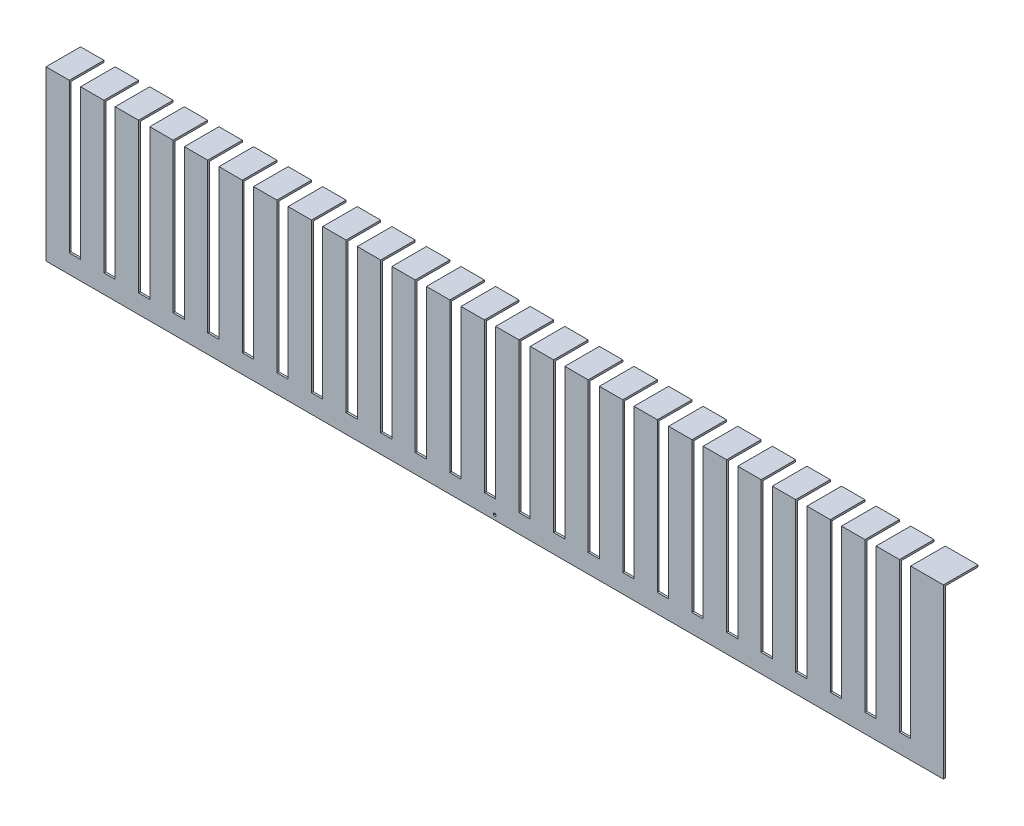
SolidWorks part; units mm, degrees
material "AISI 4130 Steel, annealed at 865C"
ref_plane "Front Plane" through (0, 0, 0) normal (0, 0, 1) x (1, 0, 0)
ref_plane "Top Plane" through (0, 0, 0) normal (0, 1, 0) x (1, 0, 0)
ref_plane "Right Plane" through (0, 0, 0) normal (1, 0, 0) x (0, 0, -1)
sketch "Sketch1" plane through (0, 0, 0) normal (0, 0, 1) x (1, 0, 0)
  line L0 (-480, 80) -> (-455, 80)
  line L1 (-480, -100) -> (480, -100)
  line L2 (-480, -100) -> (-480, 80)
  line L4 (480, -100) -> (480, 80)
  line L6 (-443, 80) -> (-418, 80)
  line L8 (-455, 80) -> (-455, -80)
  line L9 (-455, -80) -> (-443, -80)
  line L10 (-443, 80) -> (-443, -80)
  line L11 (-469.94, 80) -> (-455, 80)
  line L13 (-418, 80) -> (-418, -80)
  line L14 (-418, -80) -> (-406, -80)
  line L16 (-406, 80) -> (-406, -80)
  line L17 (-406, 80) -> (-381, 80)
  line L18 (-381, 80) -> (-381, -80)
  line L20 (-381, -80) -> (-369, -80)
  line L21 (-369, 80) -> (-369, -80)
  line L22 (-369, 80) -> (-344, 80)
  line L23 (-344, 80) -> (-344, -80)
  line L24 (-344, -80) -> (-332, -80)
  line L25 (-332, 80) -> (-332, -80)
  line L26 (-332, 80) -> (-307, 80)
  line L27 (-307, 80) -> (-307, -80)
  line L28 (-307, -80) -> (-295, -80)
  line L29 (-295, 80) -> (-295, -80)
  line L30 (-295, 80) -> (-270, 80)
  line L31 (-270, 80) -> (-270, -80)
  line L32 (-270, -80) -> (-258, -80)
  line L33 (-258, 80) -> (-258, -80)
  line L34 (-258, 80) -> (-233, 80)
  line L35 (-233, 80) -> (-233, -80)
  line L36 (-233, -80) -> (-221, -80)
  line L37 (-221, 80) -> (-221, -80)
  line L38 (-221, 80) -> (-196, 80)
  line L39 (-196, 80) -> (-196, -80)
  line L40 (-196, -80) -> (-184, -80)
  line L41 (-184, 80) -> (-184, -80)
  line L42 (-184, 80) -> (-159, 80)
  line L43 (-159, 80) -> (-159, -80)
  line L44 (-159, -80) -> (-147, -80)
  line L45 (-147, 80) -> (-147, -80)
  line L46 (-147, 80) -> (-122, 80)
  line L47 (-122, 80) -> (-122, -80)
  line L48 (-122, -80) -> (-110, -80)
  line L49 (-110, 80) -> (-110, -80)
  line L50 (-110, 80) -> (-85, 80)
  line L51 (-85, 80) -> (-85, -80)
  line L52 (-85, -80) -> (-73, -80)
  line L53 (-73, 80) -> (-73, -80)
  line L54 (-73, 80) -> (-48, 80)
  line L55 (-48, 80) -> (-48, -80)
  line L56 (-48, -80) -> (-36, -80)
  line L57 (-36, 80) -> (-36, -80)
  line L58 (-36, 80) -> (-11, 80)
  line L59 (-11, 80) -> (-11, -80)
  line L60 (-11, -80) -> (1, -80)
  line L61 (1, 80) -> (1, -80)
  line L62 (1, 80) -> (26, 80)
  line L63 (26, 80) -> (26, -80)
  line L64 (26, -80) -> (38, -80)
  line L65 (38, 80) -> (38, -80)
  line L66 (38, 80) -> (63, 80)
  line L67 (63, 80) -> (63, -80)
  line L68 (63, -80) -> (75, -80)
  line L69 (75, 80) -> (75, -80)
  line L70 (75, 80) -> (100, 80)
  line L71 (100, 80) -> (100, -80)
  line L72 (100, -80) -> (112, -80)
  line L73 (112, 80) -> (112, -80)
  line L74 (112, 80) -> (137, 80)
  line L75 (137, 80) -> (137, -80)
  line L76 (137, -80) -> (149, -80)
  line L77 (149, 80) -> (149, -80)
  line L78 (149, 80) -> (174, 80)
  line L79 (174, 80) -> (174, -80)
  line L80 (174, -80) -> (186, -80)
  line L81 (186, 80) -> (186, -80)
  line L82 (186, 80) -> (211, 80)
  line L83 (211, 80) -> (211, -80)
  line L84 (211, -80) -> (223, -80)
  line L85 (223, 80) -> (223, -80)
  line L86 (223, 80) -> (248, 80)
  line L87 (248, 80) -> (248, -80)
  line L88 (248, -80) -> (260, -80)
  line L89 (260, 80) -> (260, -80)
  line L90 (260, 80) -> (285, 80)
  line L91 (285, 80) -> (285, -80)
  line L92 (285, -80) -> (297, -80)
  line L93 (297, 80) -> (297, -80)
  line L94 (297, 80) -> (322, 80)
  line L95 (322, 80) -> (322, -80)
  line L96 (322, -80) -> (334, -80)
  line L97 (334, 80) -> (334, -80)
  line L98 (334, 80) -> (359, 80)
  line L99 (359, 80) -> (359, -80)
  line L100 (359, -80) -> (371, -80)
  line L101 (371, 80) -> (371, -80)
  line L102 (371, 80) -> (396, 80)
  line L103 (396, 80) -> (396, -80)
  line L104 (396, -80) -> (408, -80)
  line L105 (408, 80) -> (408, -80)
  line L106 (408, 80) -> (433, 80)
  line L107 (433, 80) -> (433, -80)
  line L108 (433, -80) -> (445, -80)
  line L109 (445, 80) -> (445, -80)
  line L110 (445, 80) -> (480, 80)
  line L127 (0, -20) -> (480, -100) construction
  line L147 (0, -20) -> (480, 80) construction
  line L388 (-151.26, -34.9763) -> (-151.26, -80) [skipped]
  line L389 (-163.26, -36.0958) -> (-163.26, -80) [skipped]
  line L390 (-161.32, -37.0721) -> (-161.32, -80) [skipped]
  line L391 (-173.32, -38.1917) -> (-173.32, -80) [skipped]
  line L392 (-171.38, -39.168) -> (-171.38, -80) [skipped]
  line L393 (-183.38, -40.2875) -> (-183.38, -80) [skipped]
  line L394 (-181.44, -41.2638) -> (-181.44, -80) [skipped]
  line L395 (-193.44, -42.3833) -> (-193.44, -80) [skipped]
  line L396 (-191.5, -43.3596) -> (-191.5, -80) [skipped]
  line L397 (-203.5, -80) -> (-191.5, -80) [skipped]
  line L398 (-213.56, -80) -> (-201.56, -80) [skipped]
  line L399 (-213.56, -46.575) -> (-213.56, -80) [skipped]
  line L400 (-211.62, -47.5513) -> (-211.62, -80) [skipped]
  line L401 (-223.62, -48.6708) -> (-223.62, -80) [skipped]
  line L402 (-221.68, -49.6471) -> (-221.68, -80) [skipped]
  line L403 (-233.68, -50.7667) -> (-233.68, -80) [skipped]
  line L404 (-231.74, -51.743) -> (-231.74, -80) [skipped]
  line L405 (-243.74, -52.8625) -> (-243.74, -80) [skipped]
  line L406 (-241.8, -53.8388) -> (-241.8, -80) [skipped]
  line L407 (-253.8, -54.9583) -> (-253.8, -80) [skipped]
  line L408 (-251.86, -55.9346) -> (-251.86, -80) [skipped]
  line L409 (-263.86, -57.0542) -> (-263.86, -80) [skipped]
  line L410 (-223.62, -80) -> (-211.62, -80) [skipped]
  line L411 (-263.86, -80) -> (-251.86, -80) [skipped]
  line L412 (-243.74, -80) -> (-231.74, -80) [skipped]
  line L413 (-253.8, -80) -> (-241.8, -80) [skipped]
  line L414 (-233.68, -80) -> (-221.68, -80) [skipped]
  line L415 (-201.56, -45.4555) -> (-201.56, -80) [skipped]
  line L416 (-203.5, -44.4792) -> (-203.5, -80) [skipped]
  line L417 (-183.38, -80) -> (-171.38, -80) [skipped]
  line L418 (-193.44, -80) -> (-181.44, -80) [skipped]
  line L419 (-173.32, -80) -> (-161.32, -80) [skipped]
  line L420 (-163.26, -80) -> (-151.26, -80) [skipped]
  line L421 (-294.04, 100) -> (-294.04, 63.3417) [skipped]
  line L422 (-292.1, 100) -> (-292.1, 64.318) [skipped]
  line L423 (-304.1, 100) -> (-304.1, 65.4375) [skipped]
  line L424 (-302.16, 100) -> (-302.16, 66.4138) [skipped]
  line L425 (-314.16, 100) -> (-314.16, 67.5333) [skipped]
  line L426 (-312.22, 100) -> (-312.22, 68.5096) [skipped]
  line L427 (-324.22, 100) -> (-324.22, 69.6292) [skipped]
  line L428 (-322.28, 100) -> (-322.28, 70.6055) [skipped]
  line L429 (-334.28, 100) -> (-334.28, 71.725) [skipped]
  line L430 (-282.04, 100) -> (-282.04, 62.2221) [skipped]
  line L431 (-283.98, 100) -> (-283.98, 61.2458) [skipped]
  line L432 (-271.98, 100) -> (-271.98, 60.1263) [skipped]
  line L433 (-273.92, 100) -> (-273.92, 59.15) [skipped]
  line L434 (-288.86, 80) -> (-283.92, 80) [skipped]
  line L435 (-288.86, 80) -> (-278.8, 80) [skipped]
  line L436 (-208.38, 80) -> (-203.44, 80) [skipped]
  line L437 (-238.56, 80) -> (-233.62, 80) [skipped]
  line L438 (-248.62, 80) -> (-243.68, 80) [skipped]
  line L439 (-248.62, 80) -> (-238.56, 80) [skipped]
  line L440 (-268.74, 80) -> (-263.8, 80) [skipped]
  line L441 (-268.74, 80) -> (-263.8, 80) [skipped]
  line L442 (-228.5, 80) -> (-223.56, 80) [skipped]
  line L443 (-213.5, 80) -> (-208.38, 80) [skipped]
  line L444 (-198.32, 80) -> (-193.38, 80) [skipped]
  line L445 (-188.26, 80) -> (-183.32, 80) [skipped]
  line L446 (-273.92, -80) -> (-261.92, -80) [skipped]
  line L447 (-261.92, -58.0305) -> (-261.92, -80) [skipped]
  line L448 (-294.04, -80) -> (-282.04, -80) [skipped]
  line L449 (-364.46, -80) -> (-352.46, -80) [skipped]
  line L450 (-344.34, -80) -> (-332.34, -80) [skipped]
  line L451 (-434.88, 80) -> (-434.88, -80) [skipped]
  line L452 (-434.88, -80) -> (-422.88, -80) [skipped]
  line L453 (-422.88, 80) -> (-422.88, -80) [skipped]
  line L454 (-424.82, 80) -> (-424.82, -80) [skipped]
  line L455 (-424.82, -80) -> (-412.82, -80) [skipped]
  line L456 (-412.82, 80) -> (-412.82, -80) [skipped]
  line L457 (-439.76, 80) -> (-414.76, 80) [skipped]
  line L458 (-414.76, 80) -> (-414.76, -80) [skipped]
  line L459 (-414.76, -80) -> (-402.76, -80) [skipped]
  line L460 (-402.76, 80) -> (-402.76, -80) [skipped]
  line L461 (-429.7, 80) -> (-404.7, 80) [skipped]
  line L462 (-404.7, 80) -> (-404.7, -80) [skipped]
  line L463 (-404.7, -80) -> (-392.7, -80) [skipped]
  line L464 (-392.7, 80) -> (-392.7, -80) [skipped]
  line L465 (-419.64, 80) -> (-394.64, 80) [skipped]
  line L466 (-394.64, 80) -> (-394.64, -80) [skipped]
  line L467 (-394.64, -80) -> (-382.64, -80) [skipped]
  line L468 (-382.64, 80) -> (-382.64, -80) [skipped]
  line L469 (-409.58, 80) -> (-384.58, 80) [skipped]
  line L470 (-384.58, 80) -> (-384.58, -80) [skipped]
  line L471 (-384.58, -80) -> (-372.58, -80) [skipped]
  line L472 (-372.58, 80) -> (-372.58, -80) [skipped]
  line L473 (-399.52, 80) -> (-374.52, 80) [skipped]
  line L474 (-374.52, 80) -> (-374.52, -80) [skipped]
  line L475 (-374.52, -80) -> (-362.52, -80) [skipped]
  line L476 (-362.52, 80) -> (-362.52, -80) [skipped]
  line L477 (-389.46, 80) -> (-364.46, 80) [skipped]
  line L478 (-364.46, 100) -> (-364.46, 78.0125) [skipped]
  line L479 (-352.46, 100) -> (-352.46, 76.893) [skipped]
  line L480 (-379.4, 80) -> (-354.4, 80) [skipped]
  line L481 (-354.4, 100) -> (-354.4, 75.9167) [skipped]
  line L482 (-354.4, -80) -> (-342.4, -80) [skipped]
  line L483 (-342.4, 100) -> (-342.4, 74.7971) [skipped]
  line L484 (-369.34, 80) -> (-344.34, 80) [skipped]
  line L485 (-344.34, 100) -> (-344.34, 73.8208) [skipped]
  line L486 (-332.34, 100) -> (-332.34, 72.7013) [skipped]
  line L487 (-359.28, 80) -> (-334.28, 80) [skipped]
  line L488 (-334.28, -80) -> (-322.28, -80) [skipped]
  line L489 (-349.22, 80) -> (-324.22, 80) [skipped]
  line L490 (-324.22, -80) -> (-312.22, -80) [skipped]
  line L491 (-339.16, 80) -> (-314.16, 80) [skipped]
  line L492 (-314.16, -80) -> (-302.16, -80) [skipped]
  line L493 (-329.1, 80) -> (-304.1, 80) [skipped]
  line L494 (-304.1, -80) -> (-292.1, -80) [skipped]
  line L495 (-319.04, 80) -> (-294.04, 80) [skipped]
  line L496 (-308.98, 80) -> (-304.04, 80) [skipped]
  line L497 (-283.98, -80) -> (-271.98, -80) [skipped]
  line L498 (-444.94, -80) -> (-432.94, -80) [skipped]
  line L499 (-432.94, 100) -> (-432.94, 93.6596) [skipped]
  line L500 (-444.94, 100) -> (-444.94, 94.7792) [skipped]
  line L501 (-449.82, 80) -> (-449.5662, 80) [skipped]
  line L502 (-459.88, 80) -> (-459.6262, 80) [skipped]
  circle A0 centre (0, -95) radius 1.5
  point P0 (0, 0)
  dimension "D4" = 3
  dimension "D1" = 180
  dimension "D2" = 960
  dimension "D3" = 5
  dimension "D5" = 25
  dimension "D7" = 160
  dimension "D8" = 12
  dimension "D6" = 30
  dimension "D9" = 25
extrude "Boss-Extrude1" add sketch "Sketch1" along normal blind 2
sketch "Sketch4" plane through (0, 80, 0) normal (0, 1, 0) x (1, 0, 0)
  line L0 (-418, 0) -> (-418, 35)
  line L1 (-455, 0) -> (-480, 0)
  line L2 (-455, 0) -> (-455, 35)
  line L3 (-455, 35) -> (-480, 35)
  line L4 (-480, 0) -> (-480, 35)
  line L5 (-418, 0) -> (-443, 0)
  line L6 (-443, 0) -> (-443, 35)
  line L7 (-418, 35) -> (-443, 35)
  line L8 (-381, 0) -> (-381, 35)
  line L9 (-381, 0) -> (-406, 0)
  line L10 (-406, 0) -> (-406, 35)
  line L11 (-381, 35) -> (-406, 35)
  line L12 (-344, 0) -> (-344, 35)
  line L13 (-344, 0) -> (-369, 0)
  line L14 (-369, 0) -> (-369, 35)
  line L15 (-344, 35) -> (-369, 35)
  line L16 (-307, 0) -> (-307, 35)
  line L17 (-307, 0) -> (-332, 0)
  line L18 (-332, 0) -> (-332, 35)
  line L19 (-307, 35) -> (-332, 35)
  line L20 (-270, 0) -> (-270, 35)
  line L21 (-270, 0) -> (-295, 0)
  line L22 (-295, 0) -> (-295, 35)
  line L23 (-270, 35) -> (-295, 35)
  line L24 (-233, 0) -> (-233, 35)
  line L25 (-233, 0) -> (-258, 0)
  line L26 (-258, 0) -> (-258, 35)
  line L27 (-233, 35) -> (-258, 35)
  line L28 (-196, 0) -> (-196, 35)
  line L29 (-196, 0) -> (-221, 0)
  line L30 (-221, 0) -> (-221, 35)
  line L31 (-196, 35) -> (-221, 35)
  line L32 (-159, 0) -> (-159, 35)
  line L33 (-159, 0) -> (-184, 0)
  line L34 (-184, 0) -> (-184, 35)
  line L35 (-159, 35) -> (-184, 35)
  line L36 (-122, 0) -> (-122, 35)
  line L37 (-122, 0) -> (-147, 0)
  line L38 (-147, 0) -> (-147, 35)
  line L39 (-122, 35) -> (-147, 35)
  line L40 (-85, 0) -> (-85, 35)
  line L41 (-85, 0) -> (-110, 0)
  line L42 (-110, 0) -> (-110, 35)
  line L43 (-85, 35) -> (-110, 35)
  line L44 (-48, 0) -> (-48, 35)
  line L45 (-48, 0) -> (-73, 0)
  line L46 (-73, 0) -> (-73, 35)
  line L47 (-48, 35) -> (-73, 35)
  line L48 (-11, 0) -> (-11, 35)
  line L49 (-11, 0) -> (-36, 0)
  line L50 (-36, 0) -> (-36, 35)
  line L51 (-11, 35) -> (-36, 35)
  line L52 (26, 0) -> (26, 35)
  line L53 (26, 0) -> (1, 0)
  line L54 (1, 0) -> (1, 35)
  line L55 (26, 35) -> (1, 35)
  line L56 (63, 0) -> (63, 35)
  line L57 (63, 0) -> (38, 0)
  line L58 (38, 0) -> (38, 35)
  line L59 (63, 35) -> (38, 35)
  line L60 (100, 0) -> (100, 35)
  line L61 (100, 0) -> (75, 0)
  line L62 (75, 0) -> (75, 35)
  line L63 (100, 35) -> (75, 35)
  line L64 (137, 0) -> (137, 35)
  line L65 (137, 0) -> (112, 0)
  line L66 (112, 0) -> (112, 35)
  line L67 (137, 35) -> (112, 35)
  line L68 (174, 0) -> (174, 35)
  line L69 (174, 0) -> (149, 0)
  line L70 (149, 0) -> (149, 35)
  line L71 (174, 35) -> (149, 35)
  line L72 (211, 0) -> (211, 35)
  line L73 (211, 0) -> (186, 0)
  line L74 (186, 0) -> (186, 35)
  line L75 (211, 35) -> (186, 35)
  line L76 (248, 0) -> (248, 35)
  line L77 (248, 0) -> (223, 0)
  line L78 (223, 0) -> (223, 35)
  line L79 (248, 35) -> (223, 35)
  line L80 (285, 0) -> (285, 35)
  line L81 (285, 0) -> (260, 0)
  line L82 (260, 0) -> (260, 35)
  line L83 (285, 35) -> (260, 35)
  line L84 (322, 0) -> (322, 35)
  line L85 (322, 0) -> (297, 0)
  line L86 (297, 0) -> (297, 35)
  line L87 (322, 35) -> (297, 35)
  line L88 (359, 0) -> (359, 35)
  line L89 (359, 0) -> (334, 0)
  line L90 (334, 0) -> (334, 35)
  line L91 (359, 35) -> (334, 35)
  line L92 (396, 0) -> (396, 35)
  line L93 (396, 0) -> (371, 0)
  line L94 (371, 0) -> (371, 35)
  line L95 (396, 35) -> (371, 35)
  line L96 (433, 0) -> (433, 35)
  line L97 (433, 0) -> (408, 0)
  line L98 (408, 0) -> (408, 35)
  line L99 (433, 35) -> (408, 35)
  line L101 (445, 0) -> (480, 0)
  line L102 (445, 0) -> (445, 35)
  line L103 (445, 35) -> (480, 35)
  line L104 (480, 0) -> (480, 35)
  dimension "D1" = 35
  dimension "D2" = 25
extrude "Boss-Extrude4" add sketch "Sketch4" against normal blind 2
sketch "Sketch5" plane through (0, 0, 2) normal (0, 0, 1) x (1, 0, 0)
  line L0 (0, -95) -> (0.513, -93.5905)
  line L1 (0, -95) -> (-0.513, -93.5905)
  line L2 (0, -87.6773) -> (0, -89.7335) construction
  circle A0 centre (0, -95) radius 1.5 construction
  arc A1 (0.513, -93.5905) -> (-0.513, -93.5905) centre (0, -95) ccw
  dimension "D1" = 160
  dimension "D2" = 160
extrude "Boss-Extrude5" add sketch "Sketch5" against normal up to surface (2 mm away) up to face at (1.5, -95, 0)
